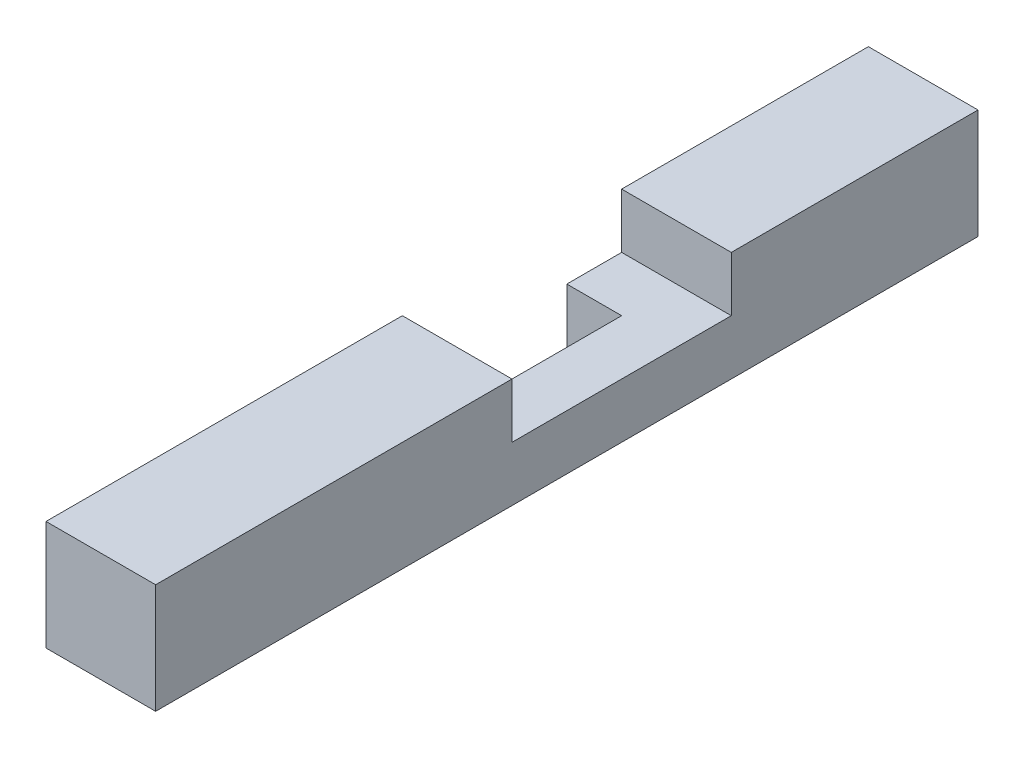
SolidWorks part; units mm, degrees
ref_plane "前基準面" through (0, 0, 0) normal (0, 0, 1) x (1, 0, 0)
ref_plane "上基準面" through (0, 0, 0) normal (0, 1, 0) x (1, 0, 0)
ref_plane "右基準面" through (0, 0, 0) normal (1, 0, 0) x (0, 0, -1)
sketch "草圖1" plane through (0, 0, 0) normal (0, 0, 1) x (1, 0, 0)
  line L1 (-2, 2) -> (2, 2)
  line L2 (-2, 2) -> (-2, -2)
  line L3 (-2, -2) -> (2, -2)
  line L4 (2, 2) -> (2, -2)
  line L5 (-2, 2) -> (2, -2) construction
  line L6 (-2, -2) -> (2, 2) construction
  point P0 (0, 0)
extrude "填料-伸長1" add sketch "草圖1" along normal blind 30 contours L1 L4 L3 L2
sketch "草圖3" plane through (-2, 0, 0) normal (-1, 0, 0) x (0, 0, 1)
  line L0 (30, -2) -> (0, -2) construction
  line L1 (0, 2) -> (9, 2)
  line L2 (0, 2) -> (0, -2)
  line L3 (0, -2) -> (9, -2)
  line L4 (9, 2) -> (9, -2)
sketch "草圖4" plane through (-2, 0, 0) normal (-1, 0, 0) x (0, 0, 1)
  line L1 (9, 2) -> (17, 2)
  line L2 (9, 2) -> (9, 0)
  line L3 (9, 0) -> (17, 0)
  line L4 (17, 2) -> (17, 0)
extrude "除料-伸長1" cut sketch "草圖4" against normal blind 4
sketch "草圖5" plane through (-2, 0, 0) normal (-1, 0, 0) x (0, 0, 1)
  line L0 (30, -2) -> (0, -2) construction
  line L1 (9, 0) -> (11, 0)
  line L2 (9, 0) -> (9, -2)
  line L3 (9, -2) -> (11, -2)
  line L4 (11, 0) -> (11, -2)
sketch "草圖6" plane through (-2, 0, 0) normal (-1, 0, 0) x (0, 0, 1)
  line L0 (30, -2) -> (0, -2) construction
  line L1 (11, 0) -> (15, 0)
  line L2 (11, 0) -> (11, -2)
  line L3 (11, -2) -> (15, -2)
  line L4 (15, 0) -> (15, -2)
extrude "除料-伸長2" cut sketch "草圖6" against normal blind 2 contours L3 L4 L1 L2
